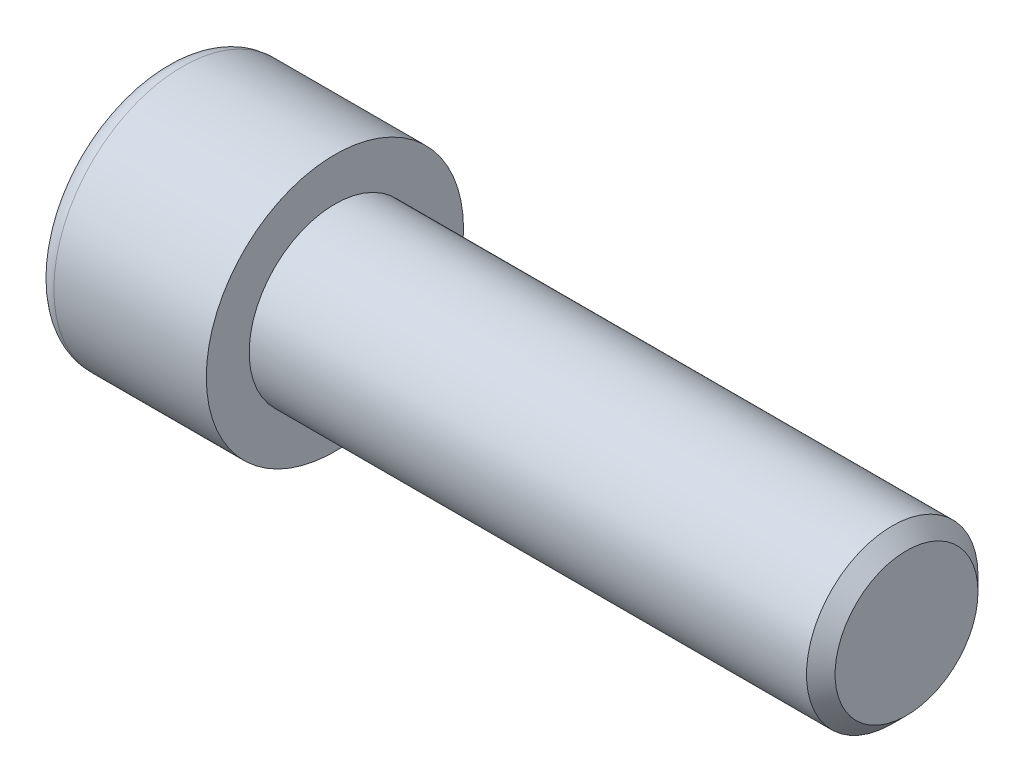
SolidWorks part; units mm, degrees
material "Latão"
ref_plane "Plano frontal" through (0, 0, 0) normal (0, 0, 1) x (1, 0, 0)
ref_plane "Plano superior" through (0, 0, 0) normal (0, 1, 0) x (1, 0, 0)
ref_plane "Plano direito" through (0, 0, 0) normal (1, 0, 0) x (0, 0, -1)
sketch "Esboço1" plane through (0, 0, 0) normal (0, 0, 1) x (1, 0, 0)
  line L0 (0, 0) -> (0, 27)
  line L1 (0, 27) -> (36, 27)
  line L2 (36, 27) -> (36, 18)
  line L3 (36, 18) -> (156, 18)
  line L4 (156, 18) -> (156, 0)
  line L5 (156, 0) -> (0, 0)
  point P5 (33.6461, 27)
  dimension "D1" = 27
  dimension "D2" = 18
  dimension "D3" = 120
  dimension "D4" = 36
revolve "Revolução1" add sketch "Esboço1" angle 360 about L5
sketch "Esboço2" plane through (0, 0, 0) normal (-1, 0, 0) x (0, 0, 1)
  line L1 (0, 15.5885) -> (-13.5, 7.7942)
  line L2 (-13.5, 7.7942) -> (-13.5, -7.7942)
  line L3 (-13.5, -7.7942) -> (0, -15.5885)
  line L4 (0, -15.5885) -> (13.5, -7.7942)
  line L5 (13.5, -7.7942) -> (13.5, 7.7942)
  line L6 (13.5, 7.7942) -> (0, 15.5885)
  circle A0 centre (0, 0) radius 13.5 construction
  dimension "D1" = 27
extrude "Corte-extrusão1" cut sketch "Esboço2" against normal blind 20 contours L1 L2 L3 L4 L5 L6
sketch "Esboço3" plane through (20, 0, 0) normal (-1, 0, 0) x (0, 0, 1)
  point P0 (0, 0)
hole_wizard "Furo de diâmetro Ø27.0 (27)1" positions "Esboço3" profile "Esboço4" hole size "Ø27.0" standard "DIN"
sketch "Esboço4" plane through (20, 0, 0) normal (0, 1, 0) x (0, 0, 1)
  line L0 (0, 0) -> (0, 13.1116)
  line L1 (0, 13.1116) -> (13.5, 5)
  line L2 (13.5, 5) -> (13.5, 0)
  line L5 (13.5, 0) -> (0, 0)
  line L10 (0, 13.1116) -> (-13.5, 5) construction
  line L11 (0, -6.35) -> (0, 107.95) construction
  dimension "Hole Dia." = 27
  dimension "Hole Depth" = 5
  dimension "Drill Angle" = 118
fillet "Filete1" radius 4 1 edges at (0, 0, -27)
chamfer "Chanfro1" distance 3 angle 45 1 edges at (156, 0, -18)
cosmetic thread "Representação de rosca1" parameters "D1"=87, "D2"=31.61
